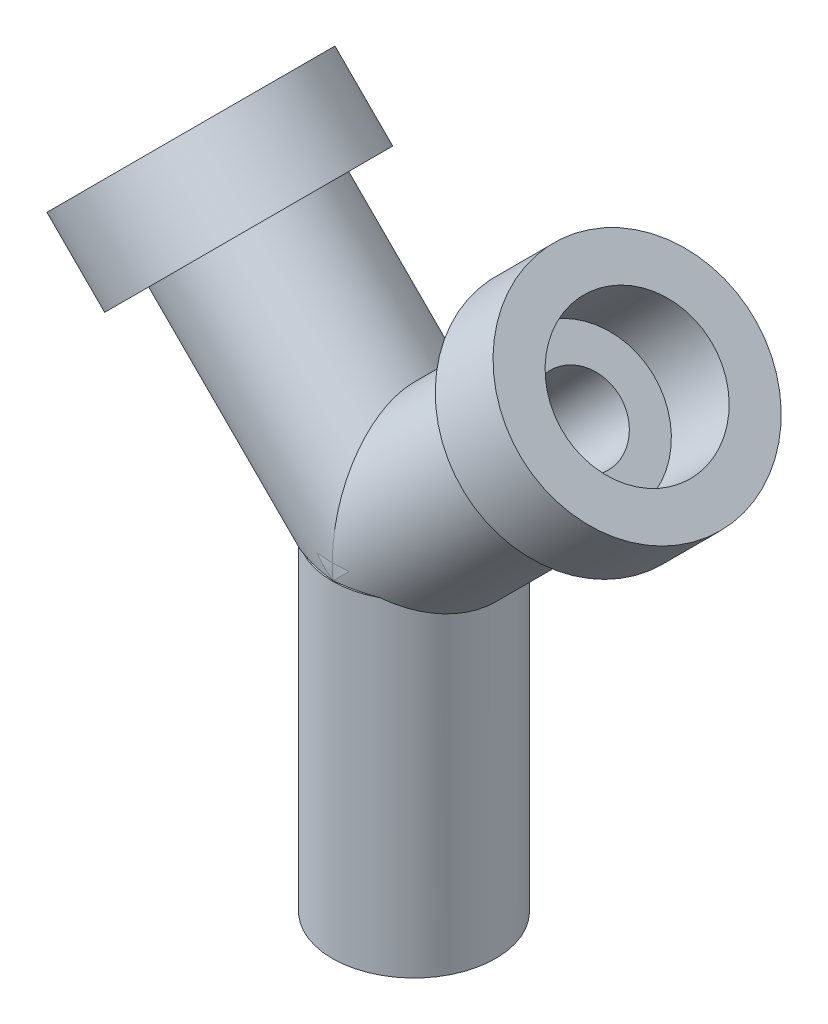
SolidWorks part; units mm, degrees
ref_plane "Front Plane" through (0, 0, 0) normal (0, 0, 1) x (1, 0, 0)
ref_plane "Top Plane" through (0, 0, 0) normal (0, 1, 0) x (1, 0, 0)
ref_plane "Right Plane" through (0, 0, 0) normal (1, 0, 0) x (0, 0, -1)
sketch "Sketch2" plane through (0, 0, 0) normal (0, 0, 1) x (1, 0, 0)
  line L0 (-8.2398, 40.3268) -> (-8.2398, -7.6751) construction
  line L1 (-8.2398, -7.6751) -> (5.2306, 5.7953) construction
  line L2 (5.2306, 5.7953) -> (1.0996, 9.9262)
  line L3 (0.7404, 10.2854) -> (-12.73, -3.1849)
  line L4 (-12.73, -3.1849) -> (-8.2398, -7.6751)
  line L5 (-8.2398, -7.6751) -> (5.2306, 5.7953)
  line L6 (2.8957, 8.1302) -> (6.8299, 12.0644) construction
  line L7 (1.0996, 9.9262) -> (5.5898, 14.4164)
  line L8 (5.5898, 14.4164) -> (3.2549, 16.7512)
  line L9 (3.2549, 16.7512) -> (-1.2352, 12.2611)
  line L10 (-1.2352, 12.2611) -> (0.7404, 10.2854)
  point P10 (-0.4306, 11.4565)
  point P13 (0, 0)
  point P14 (0, 0)
  dimension "D1" = 45
  dimension "D2" = 19.05
  dimension "D3" = 0
  dimension "D4" = 3.302
  dimension "D5" = 2.54
  dimension "D6" = 6.35
  dimension "D7" = 3.302
  dimension "D8" = 6.35
revolve "Revolve1" add sketch "Sketch2" angle 360 about L5
ref_plane "Plane1" through (-7.62, 0, 0) normal (1, 0, 0) x (0, 0, -1)
mirror "Mirror1" about plane through (-7.62, 0, 0) normal (1, 0, 0) of "Revolve1"
sketch "Sketch3" plane through (0, 0, 0) normal (0, 0, 1) x (1, 0, 0)
  line L0 (-7.62, -8.2949) -> (-7.62, -28.4933) construction
  line L3 (-7.62, -8.2949) -> (-1.27, -8.2949)
  line L4 (-7.62, -8.2949) -> (-7.62, -33.6949)
  line L5 (-7.62, -33.6949) -> (-1.27, -33.6949)
  line L6 (-1.27, -8.2949) -> (-1.27, -33.6949)
  dimension "D1" = 25.4
  dimension "D2" = 6.35
revolve "Revolve2" add sketch "Sketch3" angle 360 about L0
sketch "Sketch4" plane through (-13.1329, 13.1329, 0) normal (-0.7071, 0.7071, 0) x (0, 0, 1)
  circle A0 centre (0, -10.377) radius 3.175
  dimension "D1" = 6.35
extrude "Cut-Extrude1" cut sketch "Sketch4" against normal blind 19.05
mirror "Mirror2" about plane through (-7.62, 0, 0) normal (1, 0, 0) of "Cut-Extrude1"
sketch "Sketch6" plane through (0, -33.6949, 0) normal (0, -1, 0) x (1, 0, 0)
  circle A0 centre (-7.62, 0) radius 3.175
  dimension "D1" = 6.35
extrude "Cut-Extrude2" cut sketch "Sketch6" against normal blind 25.4
